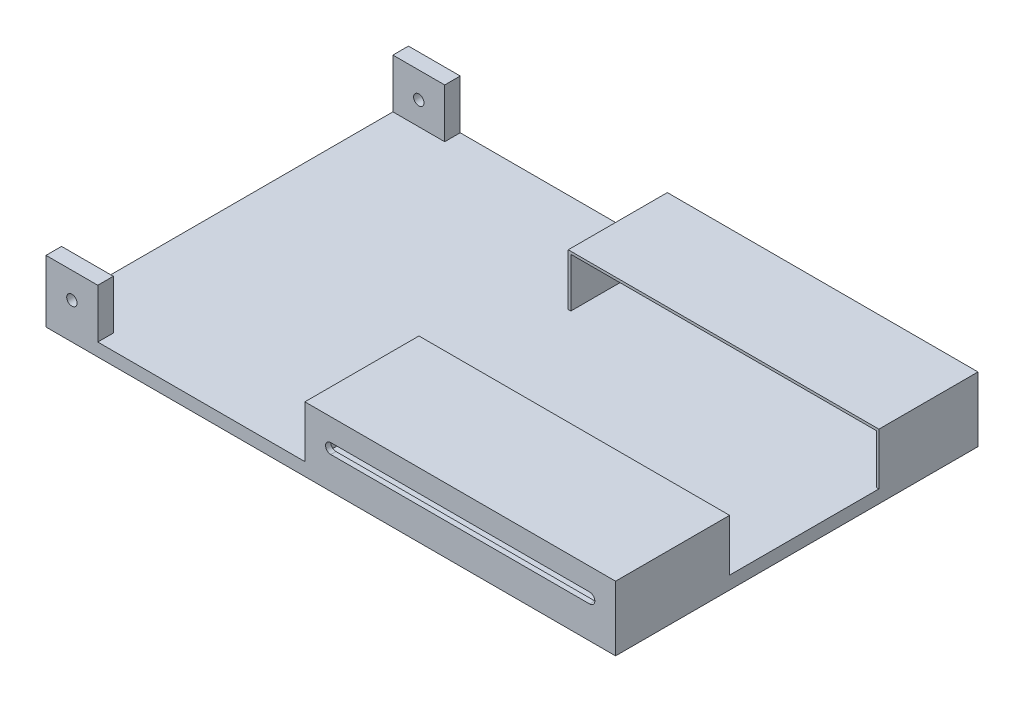
SolidWorks part; units mm, degrees
ref_plane "Front Plane" through (0, 0, 0) normal (0, 0, 1) x (1, 0, 0)
ref_plane "Top Plane" through (0, 0, 0) normal (0, 1, 0) x (1, 0, 0)
ref_plane "Right Plane" through (0, 0, 0) normal (1, 0, 0) x (0, 0, -1)
sketch "Sketch1" plane through (0, 0, 0) normal (0, 1, 0) x (1, 0, 0)
  line L1 (-55, -35) -> (55, -35)
  line L2 (-55, -35) -> (-55, 35)
  line L3 (-55, 35) -> (55, 35)
  line L4 (55, -35) -> (55, 35)
  line L5 (-55, -35) -> (55, 35) construction
  line L6 (-55, 35) -> (55, -35) construction
  point P0 (0, 0)
  dimension "D1" = 110
  dimension "D2" = 70
extrude "Boss-Extrude1" add sketch "Sketch1" against normal blind 2.5
sketch "Sketch2" plane through (0, 0, 35) normal (0, 0, 1) x (1, 0, 0)
  line L0 (55, -2.5) -> (-5, -2.5)
  line L2 (-5, -2.5) -> (-5, 9.5)
  line L3 (-5, 9.5) -> (55, 9.5)
  line L4 (55, 9.5) -> (55, -2.5)
  line L5 (-55, -2.5) -> (55, -2.5) construction
  dimension "D1" = 60
  dimension "D2" = 12
extrude "Boss-Extrude2" add sketch "Sketch2" against normal blind 1
mirror "Mirror1" about plane through (0, 0, 0) normal (0, 0, 1) of "Boss-Extrude2"
sketch "Sketch3" plane through (0, 0, 35) normal (0, 0, 1) x (1, 0, 0)
  line L0 (-5, 9.5) -> (-55, 9.5) construction
  line L1 (-55, -2.5) -> (-55, 9.5)
  line L2 (-55, 9.5) -> (-45, 9.5)
  line L3 (-45, 9.5) -> (-45, -2.5)
  line L5 (-55, -2.5) -> (55, -2.5) construction
  line L6 (-55, -2.5) -> (-45, -2.5)
  dimension "D1" = 10
extrude "Boss-Extrude3" add sketch "Sketch3" against normal blind 3
mirror "Mirror2" about plane through (0, 0, 0) normal (0, 0, 1) of "Boss-Extrude3"
sketch "Sketch5" plane through (55, 0, 0) normal (1, 0, 0) x (0, 0, -1)
  line L0 (-34, 9.5) -> (-26, 9.5)
  line L1 (-26, 9.5) -> (-26, 0)
  line L2 (-34, 0) -> (34, 0) construction
  line L3 (-26, 0) -> (-34, 0)
  line L4 (-34, 0) -> (-34, 9.5)
  line L5 (34, 9.5) -> (27, 9.5)
  line L6 (27, 9.5) -> (27, 0)
  line L7 (27, 0) -> (34, 0)
  line L8 (34, 0) -> (34, 9.5)
  dimension "D1" = 8
extrude "Boss-Extrude4" add sketch "Sketch5" against normal blind 0.5 separate body
sketch "Sketch6" plane through (-5, 0, 0) normal (-1, 0, 0) x (0, 0, 1)
  line L0 (34, 0) -> (34, 9.5) construction
  line L1 (34, 9.5) -> (26, 9.5) construction
  line L2 (26, 9.5) -> (26, 0) construction
  line L3 (26, 0) -> (34, 0) construction
  line L4 (-27, 0) -> (-27, 9.5) construction
  line L5 (-27, 9.5) -> (-34, 9.5) construction
  line L6 (-34, 9.5) -> (-34, 0) construction
  line L7 (-34, 0) -> (-27, 0) construction
  line L8 (34, 0) -> (34, 9.5)
  line L9 (34, 9.5) -> (26, 9.5)
  line L10 (26, 9.5) -> (26, 0)
  line L11 (26, 0) -> (34, 0)
  line L12 (-27, 0) -> (-27, 9.5)
  line L13 (-27, 9.5) -> (-34, 9.5)
  line L14 (-34, 9.5) -> (-34, 0)
  line L15 (-34, 0) -> (-27, 0)
extrude "Boss-Extrude5" add sketch "Sketch6" against normal blind 0.5
sketch "Sketch7" plane through (0, 9.5, 0) normal (0, 1, 0) x (1, 0, 0)
  line L0 (55, -12.9708) -> (-5, -12.9708)
  line L1 (-5, -12.9708) -> (-5, -35)
  line L2 (-5, -35) -> (55, -35)
  line L3 (55, -35) -> (55, -12.9708)
  line L4 (55, 15.8611) -> (-5, 15.8611)
  line L5 (-5, 15.8611) -> (-5, 35)
  line L6 (-5, 35) -> (55, 35)
  line L7 (55, 35) -> (55, 15.8611)
extrude "Boss-Extrude6" add sketch "Sketch7" along normal blind 0.5
sketch "Sketch10" plane through (0, 0, -35) normal (0, 0, -1) x (-1, 0, 0)
  line L0 (5, 10) -> (5, 0) construction
  line L1 (-55, -2.5) -> (-55, 10) construction
  line L2 (0, 3.6897) -> (-50, 3.6897)
  line L3 (0, 5.6897) -> (-50, 5.6897)
  arc A0 (0, 3.6897) -> (0, 5.6897) centre (0, 4.6897) ccw
  arc A1 (-50, 5.6897) -> (-50, 3.6897) centre (-50, 4.6897) ccw
  dimension "D1" = 5
  dimension "D2" = 2
  dimension "D4" = 2
  dimension "D3" = 5
extrude "Cut-Extrude1" cut sketch "Sketch10" against normal up to surface (70 mm away)
sketch "Sketch11" plane through (0, 0, -35) normal (0, 0, -1) x (-1, 0, 0)
  line L0 (55, -2.5) -> (55, 9.5) construction
  line L1 (45, 9.5) -> (55, 9.5) construction
  circle A0 centre (50, 4.5) radius 1
  dimension "D1" = 2
  dimension "D2" = 5
  dimension "D3" = 5
extrude "Cut-Extrude2" cut sketch "Sketch11" against normal up to surface (70 mm away)
sketch "Sketch12" plane through (-5, 0, 0) normal (-1, 0, 0) x (0, 0, 1)
  line L0 (-15.8611, 9.5) -> (-15.8611, 0)
  line L2 (-32, 0) -> (32, 0) construction
  line L3 (-15.8611, 0) -> (-26.9297, 0)
  line L4 (-26.9297, 0) -> (-27, 9.5)
  line L5 (-27, 9.5) -> (-15.8611, 9.5)
  line L6 (12.9708, 9.5) -> (12.9708, 0)
  line L7 (12.9708, 0) -> (26, 0)
  line L8 (26, 0) -> (26, 9.5)
  line L9 (26, 9.5) -> (26, 0) construction
  line L10 (12.9708, 9.5) -> (26, 9.5) construction
  line L11 (26, 9.5) -> (12.9708, 9.5)
extrude "Boss-Extrude7" add sketch "Sketch12" against normal blind 0.5
sketch "Sketch13" plane through (55, 0, 0) normal (1, 0, 0) x (0, 0, -1)
  line L0 (-12.9708, 9.5) -> (-12.9708, 0)
  line L1 (-12.9708, 0) -> (-26, 0)
  line L2 (-26, 0) -> (-26, 9.5)
  line L3 (-26, 9.5) -> (-12.9708, 9.5)
  line L4 (15.8611, 9.5) -> (15.8611, 0)
  line L5 (15.8611, 0) -> (27, 0)
  line L6 (27, 0) -> (27, 9.5)
  line L7 (27, 9.5) -> (15.8611, 9.5)
extrude "Boss-Extrude8" add sketch "Sketch13" against normal blind 0.5
